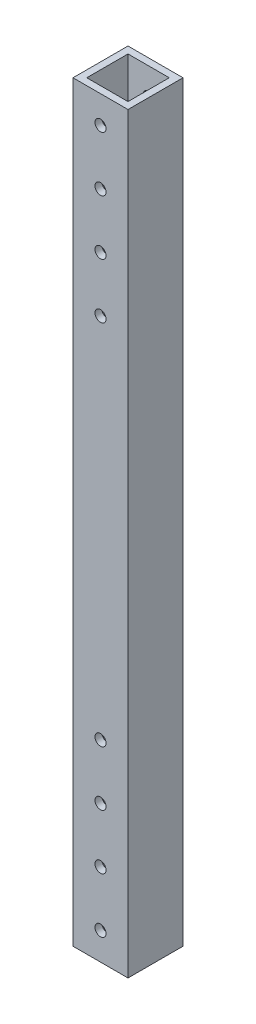
SolidWorks part; units mm, degrees
material "6061 Alloy"
ref_plane "Front" through (0, 0, 0) normal (0, 0, 1) x (1, 0, 0)
ref_plane "Top" through (0, 0, 0) normal (0, 1, 0) x (1, 0, 0)
ref_plane "Right" through (0, 0, 0) normal (1, 0, 0) x (0, 0, -1)
sketch "Sketch1" plane through (0, 0, 0) normal (0, 1, 0) x (1, 0, 0)
  line L1 (-9.525, 9.525) -> (9.525, 9.525)
  line L2 (-9.525, 9.525) -> (-9.525, -9.525)
  line L3 (-9.525, -9.525) -> (9.525, -9.525)
  line L4 (9.525, 9.525) -> (9.525, -9.525)
  line L5 (-9.525, 9.525) -> (9.525, -9.525) construction
  line L6 (-9.525, -9.525) -> (9.525, 9.525) construction
  line L7 (-12.7, 12.7) -> (12.7, 12.7)
  line L8 (-12.7, 12.7) -> (-12.7, -12.7)
  line L9 (-12.7, -12.7) -> (12.7, -12.7)
  line L10 (12.7, 12.7) -> (12.7, -12.7)
  line L11 (-12.7, 12.7) -> (12.7, -12.7) construction
  line L12 (-12.7, -12.7) -> (12.7, 12.7) construction
  point P0 (0, 0)
  point P6 (0, 0)
  dimension "D1" = 3.175
  dimension "D2" = 3.175
  dimension "D3" = 25.4
  dimension "D4" = 25.4
extrude "Boss-Extrude1" add sketch "Sketch1" along normal blind 347.345
hole_wizard "#10 Clearance Hole1" positions "Sketch2" profile "Sketch3" hole size "#10" standard "ANSI Inch" end condition through all
sketch "Sketch2" plane through (0, 0, 12.7) normal (0, 0, 1) x (1, 0, 0)
  line L0 (-12.7, 173.6725) -> (12.7, 173.6725) construction
  line L1 (-12.7, 347.345) -> (-12.7, 0) construction
  line L2 (12.7, 347.345) -> (12.7, 0) construction
  line L4 (0, 173.6725) -> (0, 0) construction
  line L5 (-12.7, 0) -> (12.7, 0) construction
  point P13 (0, 12.7)
  point P15 (0, 38.1)
  point P17 (0, 63.5)
  point P22 (0, 334.645)
  point P23 (0, 309.245)
  point P24 (0, 283.845)
  dimension "D1" = 25.4
  dimension "D2" = 25.4
  dimension "D3" = 12.7
sketch "Sketch3" plane through (0, 283.845, 12.7) normal (1, 0, 0) x (0, -1, 0)
  line L0 (0, 0) -> (0, 25.4)
  line L1 (0, 25.4) -> (2.5527, 25.4)
  line L2 (2.5527, 25.4) -> (2.5527, 0)
  line L5 (2.5527, 0) -> (0, 0)
  line L11 (0, -6.35) -> (0, 107.95) construction
  dimension "Thru Hole Dia." = 5.1054
  dimension "Thru Hole Depth" = 25.4
hole_wizard "#10 Clearance Hole2" positions "Sketch4" profile "Sketch5" hole size "#10" standard "ANSI Inch"
sketch "Sketch4" plane through (-1665.7053, -475.5473, 15.875) normal (0, 0, 1) x (1, 0, 0)
  point P0 (1665.7053, 564.4473)
  point P3 (1665.7053, 733.9923)
sketch "Sketch5" plane through (0, 88.9, 15.875) normal (1, 0, 0) x (0, -1, 0)
  line L0 (0, 0) -> (0, 30.1078)
  line L1 (0, 30.1078) -> (2.5527, 28.574)
  line L2 (2.5527, 28.574) -> (2.5527, 0)
  line L3 (2.5527, 0) -> (0, 0)
  line L4 (0, 30.1078) -> (-2.5527, 28.574) construction
  line L5 (0, -6.35) -> (0, 107.95) construction
  dimension "Hole Dia." = 5.1054
  dimension "Hole Depth" = 28.574
  dimension "Drill Angle" = 118
